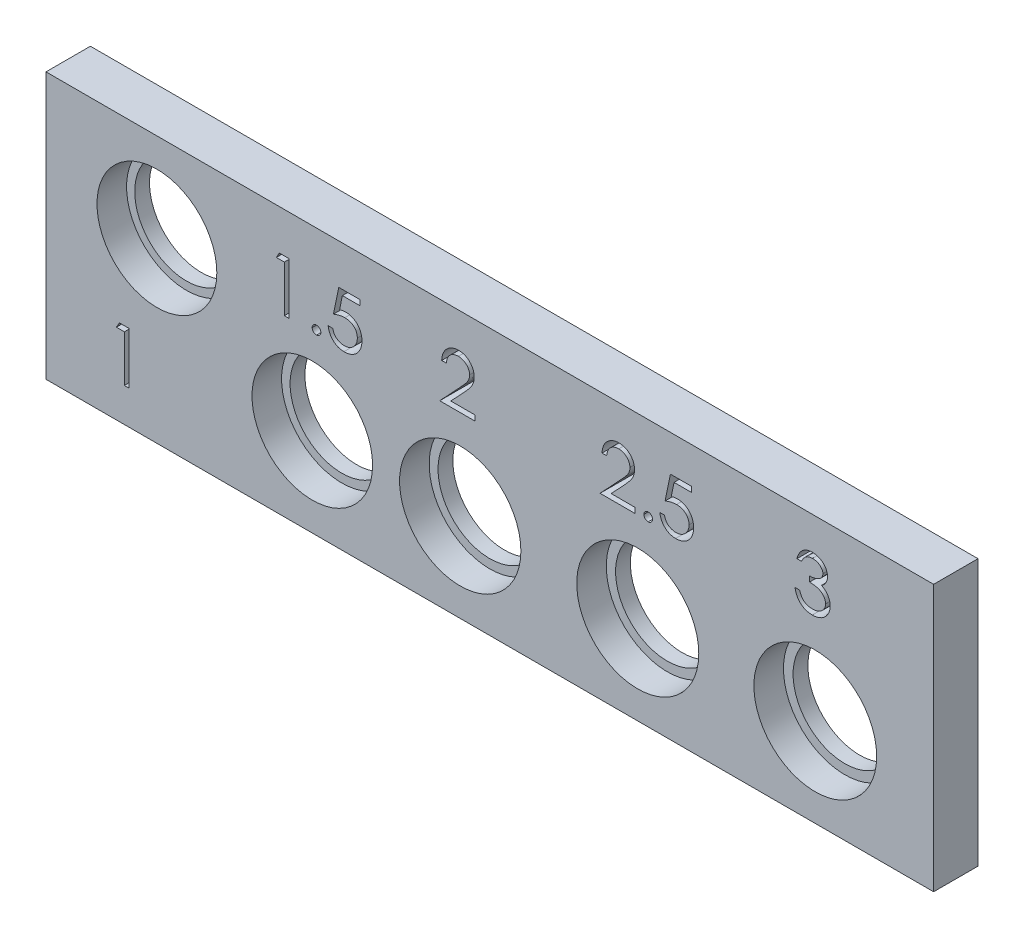
SolidWorks part; units mm, degrees
ref_plane "Front Plane" through (0, 0, 0) normal (0, 0, 1) x (1, 0, 0)
ref_plane "Top Plane" through (0, 0, 0) normal (0, 1, 0) x (1, 0, 0)
ref_plane "Right Plane" through (0, 0, 0) normal (1, 0, 0) x (0, 0, -1)
sketch "Sketch1" plane through (0, 0, 0) normal (0, 0, 1) x (1, 0, 0)
  line L1 (0, 0) -> (60, 0)
  line L2 (0, 0) -> (0, 18)
  line L3 (0, 18) -> (60, 18)
  line L4 (60, 0) -> (60, 18)
  dimension "D1" = 60
  dimension "D2" = 18
extrude "Boss-Extrude1" add sketch "Sketch1" along normal blind 3 contours L3 L4 L1 L2
sketch "Sketch2" plane through (0, 0, 3) normal (0, 0, 1) x (1, 0, 0)
  line L0 (0, 18) -> (60, 18) construction
  line L1 (60, 0) -> (60, 18) construction
  circle A0 centre (7.4967, 12) radius 4.05
  circle A1 centre (18, 6) radius 4.075
  circle A2 centre (28, 6) radius 4.1
  circle A3 centre (40, 6) radius 4.125
  circle A4 centre (52, 6) radius 4.15
  dimension "D2" = 8.1
  dimension "D3" = 8.15
  dimension "D4" = 8.2
  dimension "D5" = 8.25
  dimension "D6" = 8.3
  dimension "D7" = 8
  dimension "D1" = 6
  dimension "D8" = 12
  dimension "D9" = 12
  dimension "D10" = 10
extrude "Cut-Extrude1" cut sketch "Sketch2" against normal blind 2
sketch "Sketch3" plane through (0, 0, 1) normal (0, 0, 1) x (1, 0, 0)
  circle A0 centre (7.4967, 12) radius 3.5
  circle A1 centre (18, 6) radius 3.5
  circle A2 centre (28, 6) radius 3.5
  circle A3 centre (40, 6) radius 3.5
  circle A4 centre (52, 6) radius 3.5
extrude "Cut-Extrude2" cut sketch "Sketch3" against normal through all
sketch "Sketch6" plane through (0, 0, 3) normal (0, 0, 1) x (1, 0, 0)
  text T0 "2" font "Century Gothic" height 3.5
  text T1 "2.5" font "Century Gothic" height 3.5
  text T2 "3\r\n"
  point P1 (26.4787, 12.0536)
  point P3 (37.3177, 12.0536)
sketch "Sketch7" plane through (0, 0, 3) normal (0, 0, 1) x (1, 0, 0)
  text T0 "1.5"
  text T1 "1"
  point P1 (15.4746, 11.751)
  point P2 (14.8969, 11.7785)
  point P3 (0, 0)
extrude "Cut-Extrude3" cut sketch "Sketch7" against normal through all
extrude "Cut-Extrude4" cut sketch "Sketch6" against normal through all
